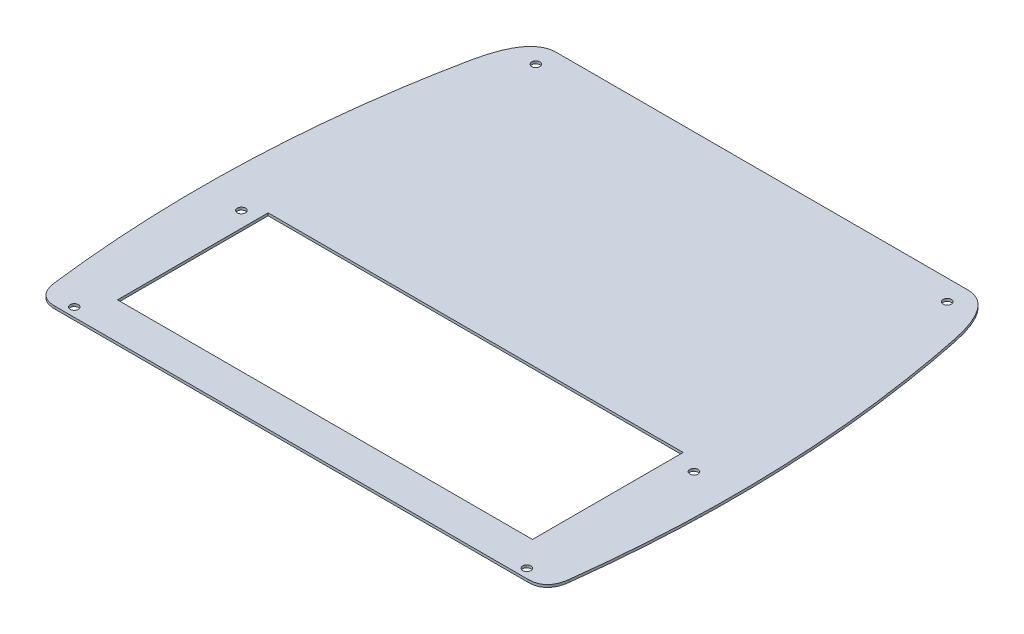
SolidWorks part; units mm, degrees
ref_plane "Front" through (0, 0, 0) normal (0, 0, 1) x (1, 0, 0)
ref_plane "Top" through (0, 0, 0) normal (0, 1, 0) x (1, 0, 0)
ref_plane "Right" through (0, 0, 0) normal (1, 0, 0) x (0, 0, -1)
sketch "Sketch1" plane through (0, 0, 0) normal (0, 1, 0) x (1, 0, 0)
  line L0 (-92, 0) -> (92, 0) construction
  line L1 (0, 0) -> (0, 183) construction
  line L2 (92, 0) -> (-92, 0)
  line L3 (-76.0494, 183) -> (-83.9506, 183) construction
  line L4 (-119.4991, 166.8074) -> (-80.5009, -150.8074) construction
  line L5 (-80, 183) -> (80, 183)
  line L6 (-106, 0) -> (-78, 0) construction
  spline S0 degree 2 poles (-100, 8) (-109.7495, 87.4037) (-94, 164) knots 0 0 0 1 1 1
  spline S1 degree 2 poles (-94, 164) (-90, 183) (-80, 183) knots 0 0 0 1 1 1
  spline S2 degree 2 poles (-92, 0) (-99, 0) (-100, 8) knots 0 0 0 1 1 1
  spline S3 degree 2 poles (92, 0) (99, 0) (100, 8) knots 0 0 0 1 1 1
  spline S4 degree 2 poles (100, 8) (109.7495, 87.4037) (94, 164) knots 0 0 0 1 1 1
  spline S5 degree 2 poles (94, 164) (90, 183) (80, 183) knots 0 0 0 1 1 1
  point P3 (0, 0)
  point P4 (0, 0)
  point P5 (0, 0)
  point P8 (88, 3.5)
  point P9 (0, 0)
  point P10 (-100, 8)
  point P11 (-103, 91.5)
  point P13 (-94, 164)
  point P19 (0, 91.5)
  point P29 (-88, 3.5)
  point P31 (0, 0)
  dimension "D2" = 3.5
  dimension "D12" = 20
  dimension "D14" = 160
  dimension "D16" = 14
  dimension "D1" = 184
  dimension "D3" = 4
  dimension "D5" = 80
  dimension "D6" = 183
  dimension "D7" = 8
  dimension "D8" = 8
  dimension "D9" = 103
  dimension "D10" = 94
  dimension "D11" = 19
  dimension "D13" = 180
  dimension "D15" = 97
  dimension "D17" = 180
extrude "Boss-Extrude1" add sketch "Sketch1" along normal blind 1 contours S0 S1 L5 S5 S4 S3 L2 S2
sketch "Sketch2" plane through (0, 1, 0) normal (0, 1, 0) x (1, 0, 0)
  line L0 (92, 0) -> (-92, 0) construction
  line L1 (0, 0) -> (0, 183) construction
  line L2 (-80, 183) -> (80, 183) construction
  line L4 (-82, 14.3) -> (79.4, 14.3)
  line L5 (-82, 14.3) -> (-82, 72.9)
  line L6 (-82, 72.9) -> (79.4, 72.9)
  line L7 (79.4, 14.3) -> (79.4, 72.9)
  line L8 (-82, 14.3) -> (79.4, 72.9) construction
  line L9 (-82, 72.9) -> (79.4, 14.3) construction
  circle A0 centre (-88, 3.5) radius 1.6
  circle A1 centre (88, 3.5) radius 1.6
  circle A2 centre (-80, 175) radius 1.6
  circle A3 centre (80, 175) radius 1.6
  circle A4 centre (-88, 68.5) radius 1.6
  circle A5 centre (88, 68.5) radius 1.6
  point P17 (-1.3, 43.6)
  point P24 (0, 0)
  point P25 (0, 0)
  point P26 (0, 0)
  dimension "D1" = 3.2
  dimension "D4" = 3.2
  dimension "D6" = 8
  dimension "D11" = 3.2
  dimension "D13" = 65
  dimension "D12" = 3.2
  dimension "D2" = 4
  dimension "D3" = 3.5
  dimension "D5" = 0
  dimension "D7" = 58.6
  dimension "D8" = 161.4
  dimension "D9" = 10.8
  dimension "D10" = 10
extrude "Cut-Extrude1" cut sketch "Sketch2" against normal through all
